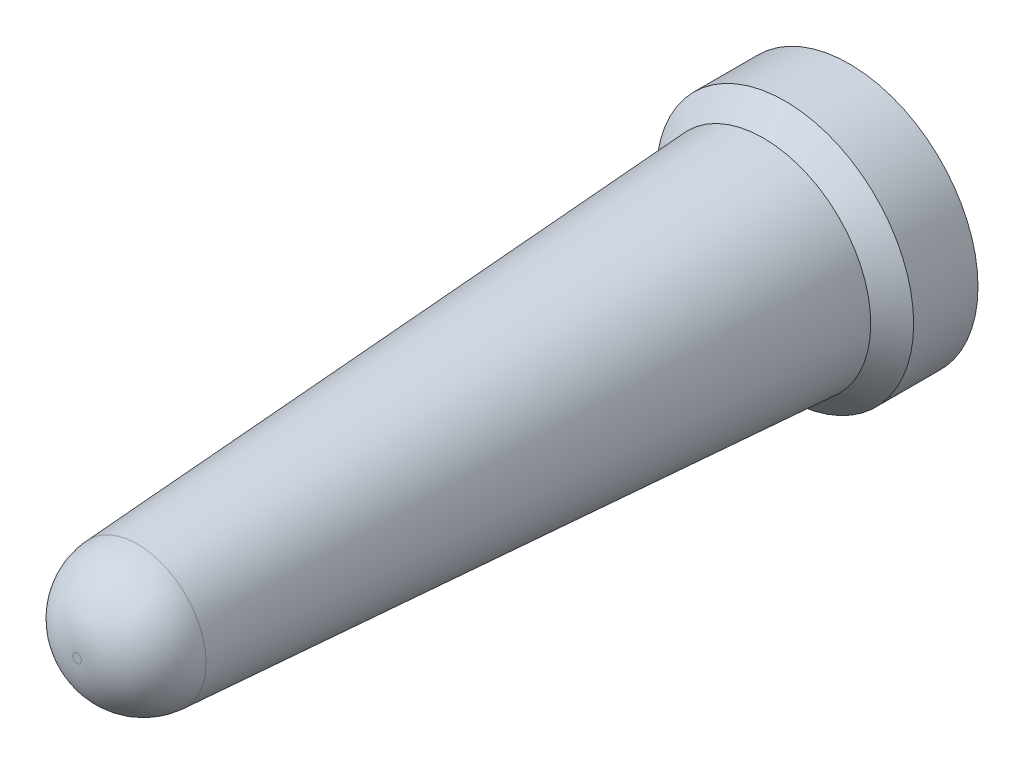
SolidWorks part; units mm, degrees
ref_plane "Front Plane" through (0, 0, 0) normal (0, 0, 1) x (1, 0, 0)
ref_plane "Top Plane" through (0, 0, 0) normal (0, 1, 0) x (1, 0, 0)
ref_plane "Right Plane" through (0, 0, 0) normal (1, 0, 0) x (0, 0, -1)
sketch "Sketch1" plane through (0, 0, 0) normal (0, 1, 0) x (1, 0, 0)
  line L0 (0.2032, 0) -> (0.381, 0)
  line L1 (0.381, 0) -> (0.381, -0.1905)
  line L2 (0.381, -0.1905) -> (0.3175, -0.254)
  line L3 (0.3175, -0.254) -> (0.2032, -2.1072)
  line L4 (0.0131, -2.286) -> (0, -2.286)
  line L5 (0, -2.286) -> (0, -0.2928)
  line L6 (0.3175, -0.254) -> (0, -0.254) construction
  line L7 (0.2032, 0) -> (0.2032, -0.1905)
  line L8 (0.2032, -0.1905) -> (0, -0.2928)
  arc A0 (0.2032, -2.1072) -> (0.0131, -2.286) centre (0.0131, -2.0955) cw
  point P0 (0.381, -0.1905)
  point P10 (0.1922, -2.286)
  dimension "D7" = 0.1905
  dimension "D1" = 0.2032
  dimension "D2" = 0.3175
  dimension "D3" = 2.032
  dimension "D4" = 2.286
  dimension "D5" = 135
  dimension "D6" = 0.381
revolve "Revolve1" add sketch "Sketch1" angle 360 about L5
